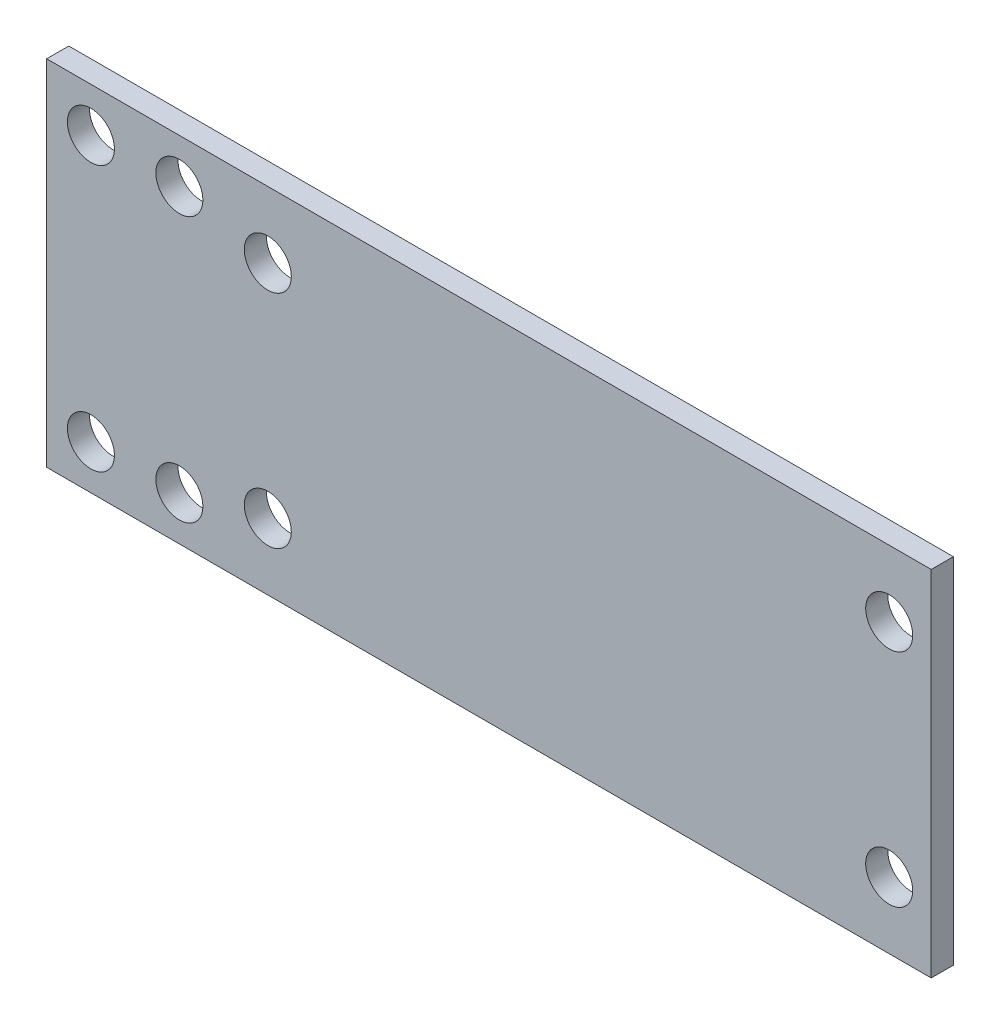
SolidWorks part; units mm, degrees
ref_plane "Front Plane" through (0, 0, 0) normal (0, 0, 1) x (1, 0, 0)
ref_plane "Top Plane" through (0, 0, 0) normal (0, 1, 0) x (1, 0, 0)
ref_plane "Right Plane" through (0, 0, 0) normal (1, 0, 0) x (0, 0, -1)
sketch "Sketch1" plane through (0, 0, 0) normal (0, 0, 1) x (1, 0, 0)
  line L1 (-75.4217, 29.1499) -> (51.5783, 29.1499)
  line L2 (-75.4217, 29.1499) -> (-75.4217, -21.6501)
  line L3 (-75.4217, -21.6501) -> (51.5783, -21.6501)
  line L4 (51.5783, 29.1499) -> (51.5783, -21.6501)
  dimension "D1" = 50.8
  dimension "D2" = 127
extrude "Boss-Extrude1" add sketch "Sketch1" along normal blind 3.175
sketch "Sketch2" plane through (0, 0, 3.175) normal (0, 0, 1) x (1, 0, 0)
  line L0 (51.5783, 29.1499) -> (-75.4217, 29.1499) construction
  line L1 (51.5783, -21.6501) -> (51.5783, 29.1499) construction
  line L2 (-75.4217, -21.6501) -> (51.5783, -21.6501) construction
  point P0 (45.5458, -12.1251)
  point P1 (45.5458, 19.6249)
  point P2 (-43.6717, -12.1251)
  point P3 (-43.6717, 19.6249)
  dimension "D1" = 9.525
  dimension "D2" = 6.0325
  dimension "D3" = 6.0325
  dimension "D4" = 9.525
  dimension "D5" = 9.525
  dimension "D6" = 9.525
  dimension "D7" = 0
  dimension "D8" = 0
hole_wizard "17/64 (0.26563) Diameter Hole1" positions "3DSketch1" profile "Sketch3" hole size "17/64" standard "ANSI Inch" end condition through all
sketch3d "3DSketch1"
  point P0 (-43.6717, 19.6249, 3.175)
  point P3 (-43.6717, -12.1251, 3.175)
  point P6 (45.5458, 19.6249, 3.175)
  point P9 (45.5458, -12.1251, 3.175)
sketch "Sketch3" plane through (-43.6717, 19.6249, 3.175) normal (1, 0, 0) x (0, -1, 0)
  line L0 (0, 0) -> (0, 3.175)
  line L1 (0, 3.175) -> (3.3735, 3.175)
  line L2 (3.3735, 3.175) -> (3.3735, 0)
  line L5 (3.3735, 0) -> (0, 0)
  line L11 (0, -6.35) -> (0, 107.95) construction
  dimension "Thru Hole Dia." = 6.747
  dimension "Thru Hole Depth" = 3.175
sketch "Sketch4" plane through (0, 0, 3.175) normal (0, 0, 1) x (1, 0, 0)
  line L0 (-75.4217, 29.1499) -> (-75.4217, -21.6501) construction
  line L1 (51.5783, 29.1499) -> (-75.4217, 29.1499) construction
  line L2 (-75.4217, -21.6501) -> (51.5783, -21.6501) construction
  point P0 (-69.0717, 22.7999)
  point P1 (-56.3717, 22.7999)
  point P2 (-69.0717, -15.3001)
  point P3 (-56.3717, -15.3001)
  dimension "D1" = 6.35
  dimension "D2" = 6.35
  dimension "D3" = 12.7
  dimension "D4" = 6.35
  dimension "D5" = 6.35
  dimension "D6" = 6.35
  dimension "D7" = 12.7
  dimension "D8" = 6.35
hole_wizard "17/64 (0.26563) Diameter Hole2" positions "3DSketch2" profile "Sketch5" hole size "17/64" standard "ANSI Inch" end condition through all
sketch3d "3DSketch2"
  point P0 (-69.0717, 22.7999, 3.175)
  point P3 (-56.3717, 22.7999, 3.175)
  point P6 (-56.3717, -15.3001, 3.175)
  point P9 (-69.0717, -15.3001, 3.175)
sketch "Sketch5" plane through (-69.0717, 22.7999, 3.175) normal (1, 0, 0) x (0, -1, 0)
  line L0 (0, 0) -> (0, 3.175)
  line L1 (0, 3.175) -> (3.3735, 3.175)
  line L2 (3.3735, 3.175) -> (3.3735, 0)
  line L5 (3.3735, 0) -> (0, 0)
  line L11 (0, -6.35) -> (0, 107.95) construction
  dimension "Thru Hole Dia." = 6.747
  dimension "Thru Hole Depth" = 3.175
